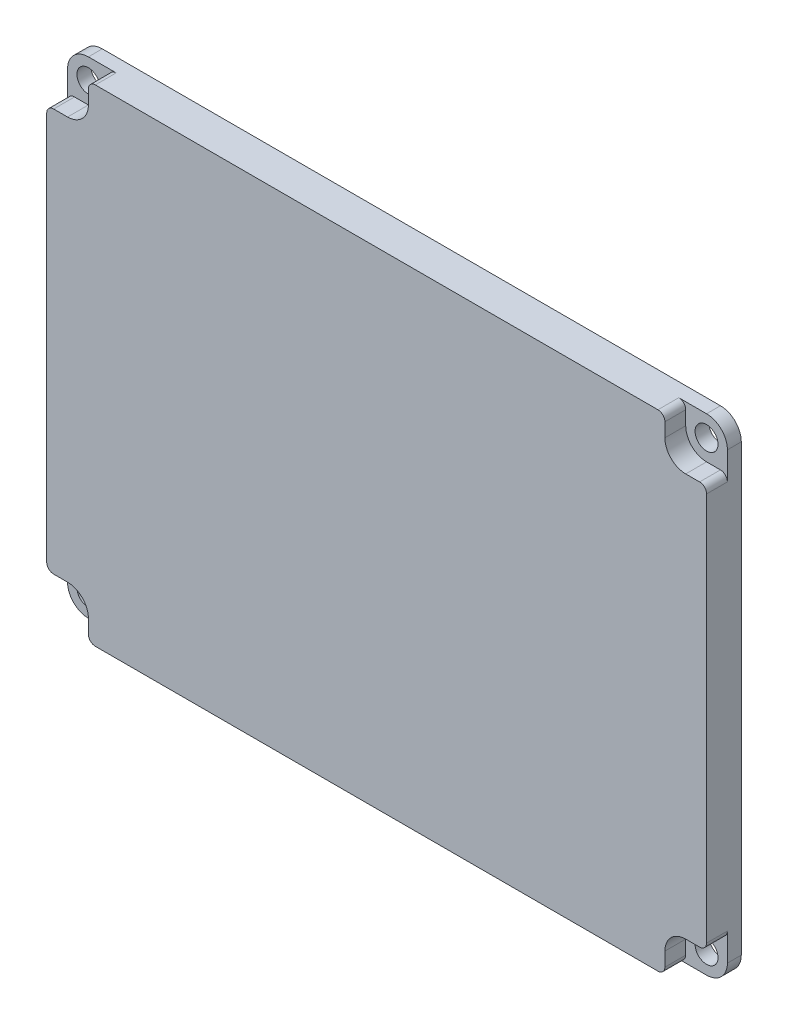
SolidWorks part; units mm, degrees
ref_plane "正面" through (0, 0, 0) normal (0, 0, 1) x (1, 0, 0)
ref_plane "平面" through (0, 0, 0) normal (0, 1, 0) x (1, 0, 0)
ref_plane "右側面" through (0, 0, 0) normal (1, 0, 0) x (0, 0, -1)
sketch "ｽｹｯﾁ1" plane through (0, 0, 0) normal (0, 0, 1) x (1, 0, 0)
  line L1 (0, 0) -> (95, 0)
  line L2 (0, 0) -> (0, 70)
  line L3 (0, 70) -> (95, 70)
  line L4 (95, 0) -> (95, 70)
  line L5 (0, 0) -> (95, 70) construction
  line L6 (0, 70) -> (95, 0) construction
  point P4 (47.5, 35)
  dimension "D1" = 95
  dimension "D2" = 70
extrude "ﾎﾞｽ - 押し出し1" add sketch "ｽｹｯﾁ1" along normal blind 5
fillet "ﾌｨﾚｯﾄ1" radius 3 4 edges at (0, 70, 2.5) (0, 0, 2.5) (95, 0, 2.5) (95, 70, 2.5)
sketch "ｽｹｯﾁ3" plane through (0, 0, 5) normal (0, 0, 1) x (1, 0, 0)
  point P0 (3, 67)
  point P1 (92, 67)
  point P3 (3, 3)
  point P5 (92, 3)
sketch "ｽｹｯﾁ13" plane through (0, 0, 5) normal (0, 0, 1) x (1, 0, 0)
  circle A0 centre (3, 67) radius 1.65
  circle A1 centre (92, 67) radius 1.65
  circle A2 centre (3, 3) radius 1.65
  circle A3 centre (92, 3) radius 1.65
  dimension "D1" = 3.3
  dimension "D2" = 3.3
  dimension "D3" = 3.3
  dimension "D4" = 3.3
extrude "ｶｯﾄ - 押し出し2" cut sketch "ｽｹｯﾁ13" against normal blind 5 contours A0 | A1 | A2 | A3
sketch "ｽｹｯﾁ14" plane through (0, 0, 5) normal (0, 0, 1) x (1, 0, 0)
  circle A0 centre (3, 67) radius 3
  circle A1 centre (92, 67) radius 3
  circle A2 centre (3, 3) radius 3
  circle A3 centre (92, 3) radius 3
extrude "ｶｯﾄ - 押し出し3" cut sketch "ｽｹｯﾁ14" against normal blind 3
sketch "ｽｹｯﾁ15" plane through (0, 0, 5) normal (0, 0, 1) x (1, 0, 0)
  line L1 (3, 64) -> (-2.1261, 64)
  line L2 (3, 64) -> (3, 67.6091)
  line L3 (3, 67.6091) -> (-2.1261, 67.6091)
  line L4 (-2.1261, 64) -> (-2.1261, 67.6091)
  line L5 (3, 64) -> (-2.1261, 67.6091) construction
  line L6 (3, 67.6091) -> (-2.1261, 64) construction
  line L7 (6, 67) -> (1.7816, 67)
  line L8 (6, 67) -> (6, 71.1643)
  line L9 (6, 71.1643) -> (1.7816, 71.1643)
  line L10 (1.7816, 67) -> (1.7816, 71.1643)
  line L11 (6, 67) -> (1.7816, 71.1643) construction
  line L12 (6, 71.1643) -> (1.7816, 67) construction
  line L13 (89, 67) -> (93.3728, 67)
  line L14 (89, 67) -> (89, 71.5326)
  line L15 (89, 71.5326) -> (93.3728, 71.5326)
  line L16 (93.3728, 67) -> (93.3728, 71.5326)
  line L17 (89, 67) -> (93.3728, 71.5326) construction
  line L18 (89, 71.5326) -> (93.3728, 67) construction
  line L19 (92, 64) -> (97.4855, 64)
  line L20 (92, 64) -> (92, 68.5624)
  line L21 (92, 68.5624) -> (97.4855, 68.5624)
  line L22 (97.4855, 64) -> (97.4855, 68.5624)
  line L23 (92, 64) -> (97.4855, 68.5624) construction
  line L24 (92, 68.5624) -> (97.4855, 64) construction
  line L25 (3, 6) -> (-2.1261, 6)
  line L26 (3, 6) -> (3, 2.4196)
  line L27 (3, 2.4196) -> (-2.1261, 2.4196)
  line L28 (-2.1261, 6) -> (-2.1261, 2.4196)
  line L29 (3, 6) -> (-2.1261, 2.4196) construction
  line L30 (3, 2.4196) -> (-2.1261, 6) construction
  line L31 (6, 3) -> (1.4494, 3)
  line L32 (6, 3) -> (6, -1.4672)
  line L33 (6, -1.4672) -> (1.4494, -1.4672)
  line L34 (1.4494, 3) -> (1.4494, -1.4672)
  line L35 (6, 3) -> (1.4494, -1.4672) construction
  line L36 (6, -1.4672) -> (1.4494, 3) construction
  line L37 (89, 3) -> (93.4874, 3)
  line L38 (89, 3) -> (89, -2.9092)
  line L39 (89, -2.9092) -> (93.4874, -2.9092)
  line L40 (93.4874, 3) -> (93.4874, -2.9092)
  line L41 (89, 3) -> (93.4874, -2.9092) construction
  line L42 (89, -2.9092) -> (93.4874, 3) construction
  line L43 (92, 6) -> (98.3623, 6)
  line L44 (92, 6) -> (92, 0.182)
  line L45 (92, 0.182) -> (98.3623, 0.182)
  line L46 (98.3623, 6) -> (98.3623, 0.182)
  line L47 (92, 6) -> (98.3623, 0.182) construction
  line L48 (92, 0.182) -> (98.3623, 6) construction
  arc A0 (0, 67) -> (3, 70) centre (3, 67) ccw construction
  arc A1 (92, 70) -> (95, 67) centre (92, 67) ccw construction
  arc A2 (3, 0) -> (0, 3) centre (3, 3) ccw construction
  arc A3 (95, 3) -> (92, 0) centre (92, 3) ccw construction
  point P4 (0.437, 65.8046)
  point P12 (3.8908, 69.0821)
  point P17 (91.1864, 69.2663)
  point P25 (94.7427, 66.2812)
  point P30 (0.437, 4.2098)
  point P38 (3.7247, 0.7664)
  point P43 (91.2437, 0.0454)
  point P51 (95.1812, 3.091)
  line M5 (95, 3) -> (95, 67)
  arc M6 (95, 67) -> (92, 70) centre (92, 67) cw
  line M7 (92, 70) -> (3, 70)
  arc M8 (3, 70) -> (0, 67) centre (3, 67) cw
  line M9 (0, 67) -> (0, 3)
  arc M10 (0, 3) -> (3, 0) centre (3, 3) cw
  line M11 (3, 0) -> (92, 0)
  arc M12 (92, 0) -> (95, 3) centre (92, 3) cw
extrude "ｶｯﾄ - 押し出し4" cut sketch "ｽｹｯﾁ15" against normal blind 3 contours L43 M12 M5 | L38 M12 M11 | L32 M10 M11 | L25 M10 M9 | L1 M8 M9 | L8 M8 M7 | L14 M6 M7 | L19 M6 M5
fillet "ﾌｨﾚｯﾄ3" radius 1 8 edges at (6, 0, 3.5) (0, 6, 3.5) (89, 0, 3.5) (95, 6, 3.5) (89, 70, 3.5) (95, 64, 3.5) (6, 70, 3.5) (0, 64, 3.5)
